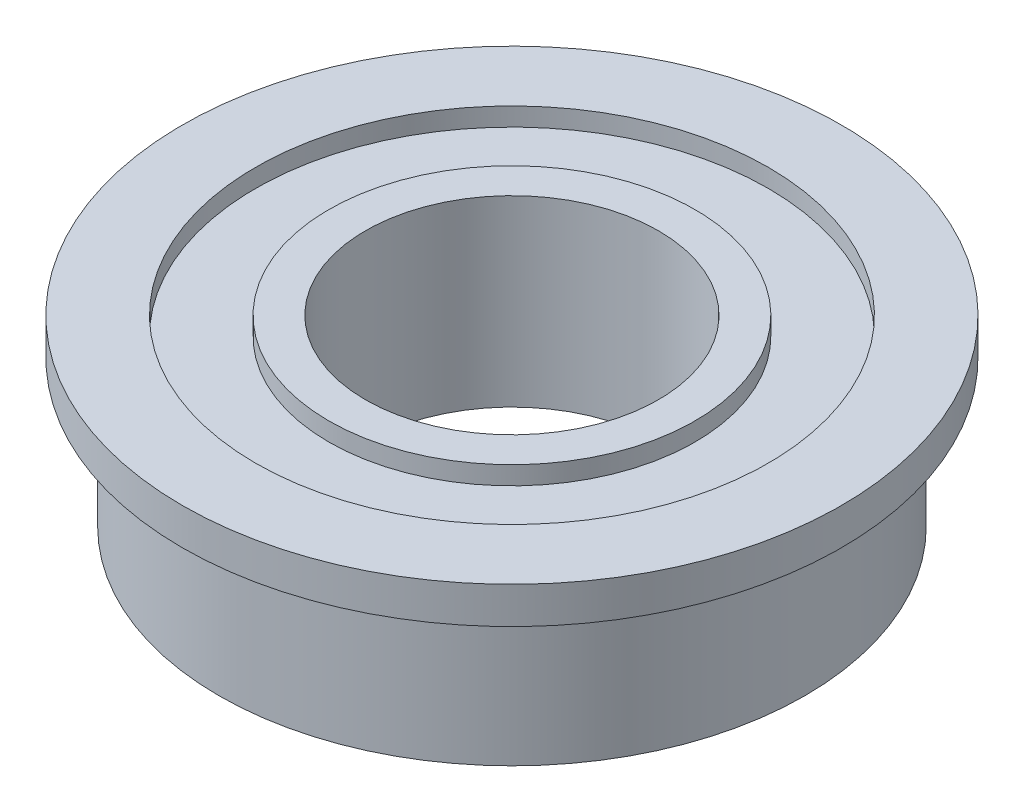
SolidWorks part; units mm, degrees
ref_plane "Front Plane" through (0, 0, 0) normal (0, 0, 1) x (1, 0, 0)
ref_plane "Top Plane" through (0, 0, 0) normal (0, 1, 0) x (1, 0, 0)
ref_plane "Right Plane" through (0, 0, 0) normal (1, 0, 0) x (0, 0, -1)
sketch "Sketch1" plane through (0, 0, 0) normal (0, 1, 0) x (1, 0, 0)
  circle A0 centre (0, 0) radius 8
  circle A1 centre (0, 0) radius 4
  dimension "D1" = 16
  dimension "D2" = 8
extrude "Boss-Extrude1" add sketch "Sketch1" along normal blind 4
sketch "Sketch2" plane through (0, 4, 0) normal (0, 1, 0) x (1, 0, 0)
  circle A0 centre (0, 0) radius 9
  circle A1 centre (0, 0) radius 4 construction
  circle A2 centre (0, 0) radius 4
  dimension "D1" = 18
extrude "Boss-Extrude2" add sketch "Sketch2" along normal blind 1
sketch "Sketch3" plane through (0, 0, 0) normal (0, -1, 0) x (1, 0, 0)
  circle A0 centre (0, 0) radius 5
  circle A1 centre (0, 0) radius 7
  dimension "D1" = 10
  dimension "D2" = 14
extrude "Cut-Extrude1" cut sketch "Sketch3" against normal blind 0.5
sketch "Sketch4" plane through (0, 5, 0) normal (0, 1, 0) x (1, 0, 0)
  circle A0 centre (0, 0) radius 5
  circle A1 centre (0, 0) radius 7
  dimension "D1" = 10
  dimension "D2" = 14
extrude "Cut-Extrude2" cut sketch "Sketch4" against normal blind 0.5
